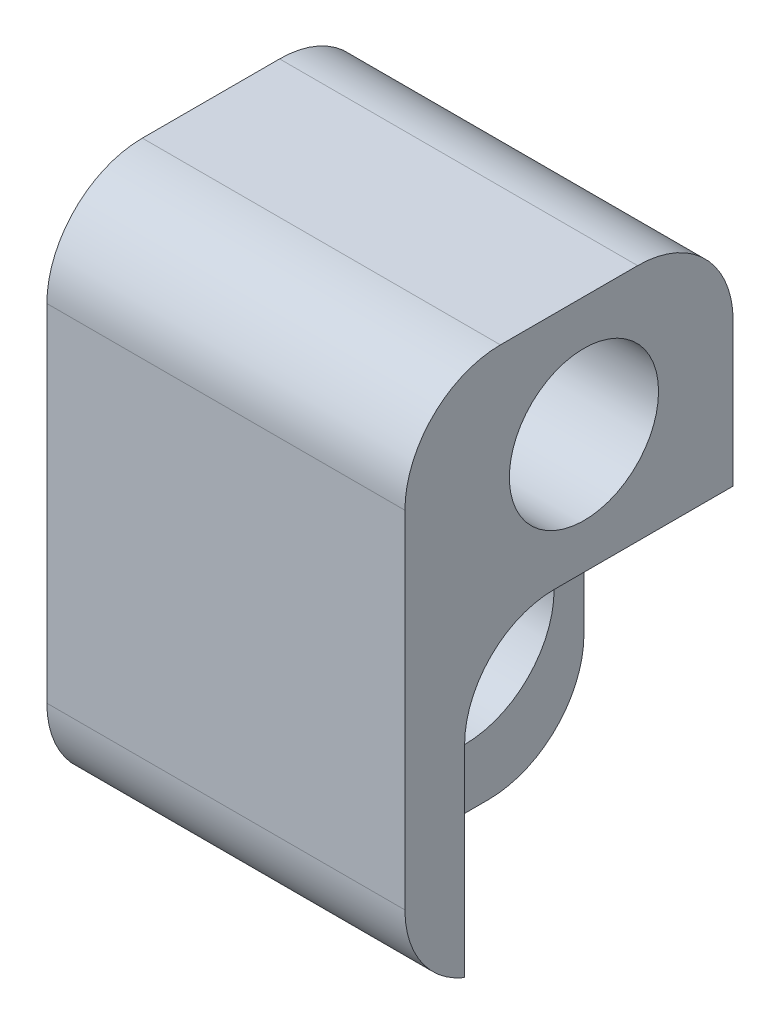
SolidWorks part; units mm, degrees
material "1060 Alloy"
ref_plane "Front Plane" through (0, 0, 0) normal (0, 0, 1) x (1, 0, 0)
ref_plane "Top Plane" through (0, 0, 0) normal (0, 1, 0) x (1, 0, 0)
ref_plane "Right Plane" through (0, 0, 0) normal (1, 0, 0) x (0, 0, -1)
sketch "Sketch1" plane through (0, 0, 0) normal (1, 0, 0) x (0, 0, -1)
  line L1 (0, 0) -> (5.5, 0)
  line L2 (0, 0) -> (0, 9)
  line L3 (0, 9) -> (5.5, 9)
  line L4 (5.5, 0) -> (5.5, 9)
  circle A0 centre (3.5, 2.5) radius 1.5
  circle A1 centre (3, 7) radius 1.25
  dimension "D3" = 3
  dimension "D6" = 2.5
  dimension "D1" = 9
  dimension "D2" = 5.5
  dimension "D4" = 2
  dimension "D5" = 2.5
  dimension "D7" = 2
  dimension "D8" = 2.5
extrude "Boss-Extrude1" add sketch "Sketch1" along normal blind 6
sketch "Sketch2" plane through (6, 0, 0) normal (1, 0, 0) x (0, 0, -1)
  line L0 (5.5, 0) -> (5.5, 9) construction
  line L1 (5.5, 5) -> (1, 5)
  line L2 (5.5, 5) -> (5.5, 0)
  line L3 (5.5, 0) -> (1, 0)
  line L4 (1, 5) -> (1, 0)
  line L5 (0, 0) -> (5.5, 0) construction
  dimension "D1" = 4.5
  dimension "D2" = 5
extrude "Cut-Extrude1" cut sketch "Sketch2" against normal blind 2.5
fillet "Fillet1" radius 1.5 1 edges at (4.75, 5, -1)
fillet "Fillet2" radius 1.6 4 edges at (3, 9, 0) (3, 0, 0) (1.75, 0, -5.5) (3, 9, -5.5)
